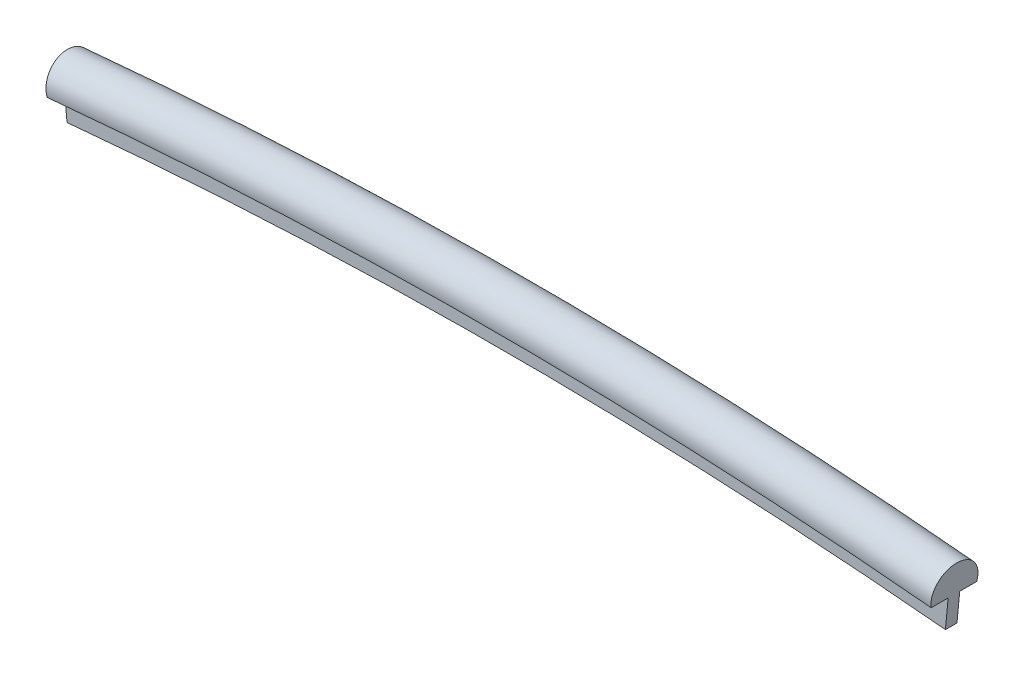
SolidWorks part; units mm, degrees
ref_plane "Front Plane" through (0, 0, 0) normal (0, 0, 1) x (1, 0, 0)
ref_plane "Top Plane" through (0, 0, 0) normal (0, 1, 0) x (1, 0, 0)
ref_plane "Right Plane" through (0, 0, 0) normal (1, 0, 0) x (0, 0, -1)
sketch "Sketch2" plane through (0, 0, 0) normal (1, 0, 0) x (0, 0, -1)
  line L0 (0, 241.3) -> (0, 0) construction
  line L2 (0, 241.3) -> (0, 239.8) construction
  line L3 (0, 239.8) -> (0.3, 239.8)
  line L4 (0, 239.8) -> (-0.3, 239.8)
  line L5 (-0.3, 239.8) -> (-0.3, 241.3)
  line L6 (0.3, 239.8) -> (0.3, 241.3)
  line L7 (0, 241.3) -> (0, 242.8) construction
  line L8 (-1.18, 241.3) -> (-0.3, 241.3)
  line L9 (0.3, 241.3) -> (1.18, 241.3)
  arc A0 (-1.18, 241.3) -> (1.18, 241.3) centre (0, 241.586) cw
  point P14 (0, 241.3)
ref_axis "Axis2" through (0, 0, 70.5976) along (0, 0, -1)
revolve "Revolve1" add sketch "Sketch2" angle 5.442 about axis through (0, 0, 70.5976) along (0, 0, -1)
